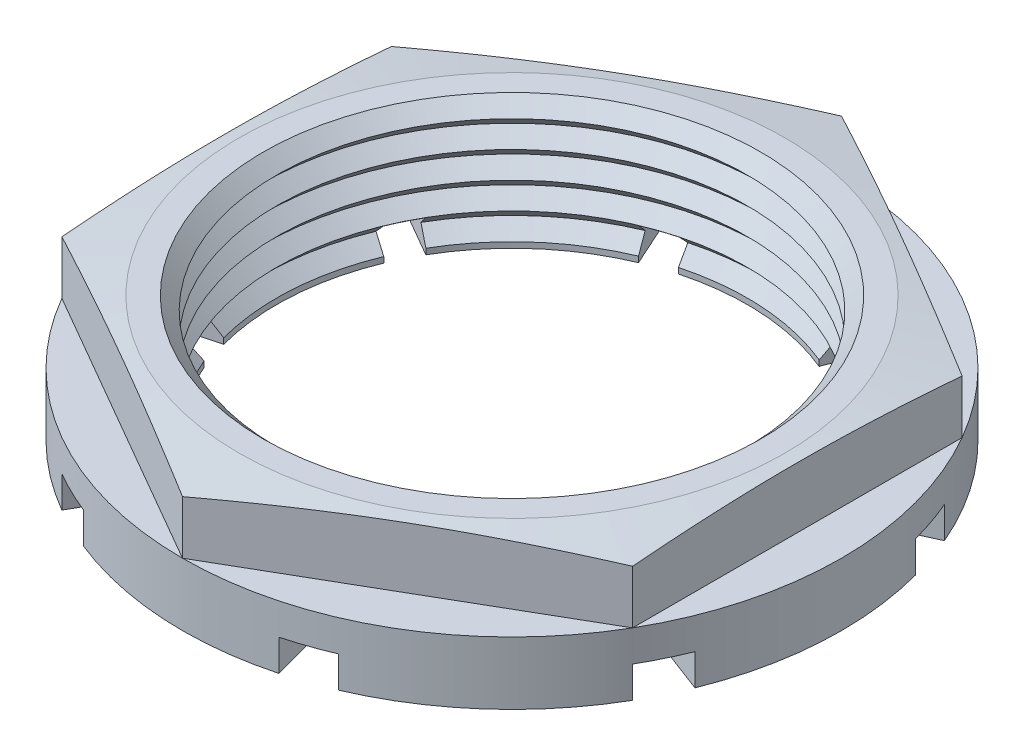
SolidWorks part; units mm, degrees
material "CA"
ref_plane "Front Plane" through (0, 0, 0) normal (0, 0, 1) x (1, 0, 0)
ref_plane "Top Plane" through (0, 0, 0) normal (0, 1, 0) x (1, 0, 0)
ref_plane "Right Plane" through (0, 0, 0) normal (1, 0, 0) x (0, 0, -1)
sketch "Sketch1" plane through (0, 0, 0) normal (1, 0, 0) x (0, 0, -1)
  line L0 (9.525, -0.9255) -> (13.335, -0.9255)
  line L1 (13.335, -0.9255) -> (13.335, 3.7735)
  line L2 (11.049, 4.1545) -> (10.0638, 4.1545)
  line L3 (0, 15.0904) -> (0, -9.0542) construction
  line L4 (11.049, 4.1545) -> (13.335, 3.7735)
  line L6 (9.525, 0.3828) -> (10.0638, 0.9216)
  line L7 (10.0638, 0.9216) -> (9.525, 1.4604)
  line L8 (9.525, 1.4604) -> (10.0638, 1.9993)
  line L9 (10.0638, 1.9993) -> (9.525, 2.5381)
  line L10 (9.525, 2.5381) -> (10.0638, 3.0769)
  line L11 (10.0638, 3.0769) -> (9.525, 3.6157)
  line L12 (9.525, 3.6157) -> (10.0638, 4.1545)
  line L13 (9.525, 0.3828) -> (10.0638, -0.156)
  line L14 (10.0638, -0.156) -> (9.525, -0.6948)
  line L15 (9.525, -0.6948) -> (9.525, -0.9255)
  dimension "D1" = 5.08
  dimension "D4" = 4.699
  dimension "D5" = 0.762
  dimension "D6" = 0.762
  dimension "D7" = 0.762
  dimension "D8" = 0.762
  dimension "D9" = 0.762
  dimension "D10" = 0.762
  dimension "D11" = 0.762
revolve "Revolve1" add sketch "Sketch1" angle 360 about L3
sketch "Sketch2" plane through (0, 4.1545, 0) normal (0, 1, 0) x (-1, 0, 0)
  line L1 (0, -13.335) -> (11.5484, -6.6675)
  line L2 (11.5484, -6.6675) -> (11.5484, 6.6675)
  line L3 (11.5484, 6.6675) -> (0, 13.335)
  line L4 (0, 13.335) -> (-11.5484, 6.6675)
  line L5 (-11.5484, 6.6675) -> (-11.5484, -6.6675)
  line L6 (-11.5484, -6.6675) -> (0, -13.335)
  circle A0 centre (0, 0) radius 11.5484 construction
extrude "Cut-Extrude1" cut sketch "Sketch2" against normal blind 2.54 flip side to cut
sketch "Sketch3" plane through (0, -0.9255, 0) normal (0, -1, 0) x (1, 0, 0)
  line L0 (0, 17.2305) -> (0, -16.7573) construction
  line L1 (-4.7625, 8.2489) -> (-6.6675, 11.5484)
  line L2 (2.4653, 9.2004) -> (3.4514, 12.8806)
  line L3 (5.2358, 12.2641) -> (3.67, 8.7896)
  line L4 (8.2489, 4.7625) -> (11.5484, 6.6675)
  line L5 (12.3743, 4.9698) -> (8.8102, 3.6201)
  line L6 (9.2004, -2.4653) -> (12.8806, -3.4514)
  line L7 (-4.9698, 12.3743) -> (-3.6201, 8.8102)
  line L8 (12.2641, -5.2358) -> (8.7896, -3.67)
  line L9 (4.7625, -8.2489) -> (6.6675, -11.5484)
  line L10 (4.9698, -12.3743) -> (3.6201, -8.8102)
  line L11 (-2.4653, -9.2004) -> (-3.4514, -12.8806)
  line L12 (-5.2358, -12.2641) -> (-3.67, -8.7896)
  line L13 (-8.2489, -4.7625) -> (-11.5484, -6.6675)
  line L14 (-12.3743, -4.9698) -> (-8.8102, -3.6201)
  line L15 (-9.2004, 2.4653) -> (-12.8806, 3.4514)
  line L16 (-12.2641, 5.2358) -> (-8.7896, 3.67)
  circle A0 centre (0, 0) radius 13.335 construction
  arc A1 (-3.6201, 8.8102) -> (-4.7625, 8.2489) centre (0, 0) ccw
  arc A2 (-4.9698, 12.3743) -> (-6.6675, 11.5484) centre (0, 0) ccw
  arc A3 (5.2358, 12.2641) -> (3.4514, 12.8806) centre (0, 0) ccw
  arc A4 (3.67, 8.7896) -> (2.4653, 9.2004) centre (0, 0) ccw
  arc A5 (12.3743, 4.9698) -> (11.5484, 6.6675) centre (0, 0) ccw
  arc A6 (8.8102, 3.6201) -> (8.2489, 4.7625) centre (0, 0) ccw
  arc A7 (12.2641, -5.2358) -> (12.8806, -3.4514) centre (0, 0) ccw
  arc A8 (8.7896, -3.67) -> (9.2004, -2.4653) centre (0, 0) ccw
  arc A9 (4.9698, -12.3743) -> (6.6675, -11.5484) centre (0, 0) ccw
  arc A10 (3.6201, -8.8102) -> (4.7625, -8.2489) centre (0, 0) ccw
  arc A11 (-5.2358, -12.2641) -> (-3.4514, -12.8806) centre (0, 0) ccw
  arc A12 (-3.67, -8.7896) -> (-2.4653, -9.2004) centre (0, 0) ccw
  arc A13 (-12.3743, -4.9698) -> (-11.5484, -6.6675) centre (0, 0) ccw
  arc A14 (-8.8102, -3.6201) -> (-8.2489, -4.7625) centre (0, 0) ccw
  arc A15 (-12.2641, 5.2358) -> (-12.8806, 3.4514) centre (0, 0) ccw
  arc A16 (-8.7896, 3.67) -> (-9.2004, 2.4653) centre (0, 0) ccw
  point P11 (1.0999, 0.635)
  point P13 (-5.5676, 12.1834)
  point P14 (1.6498, 0.9525)
  point P15 (-5.0177, 12.5009)
  dimension "D1" = 8
extrude "Cut-Extrude2" cut sketch "Sketch3" against normal blind 1.27
